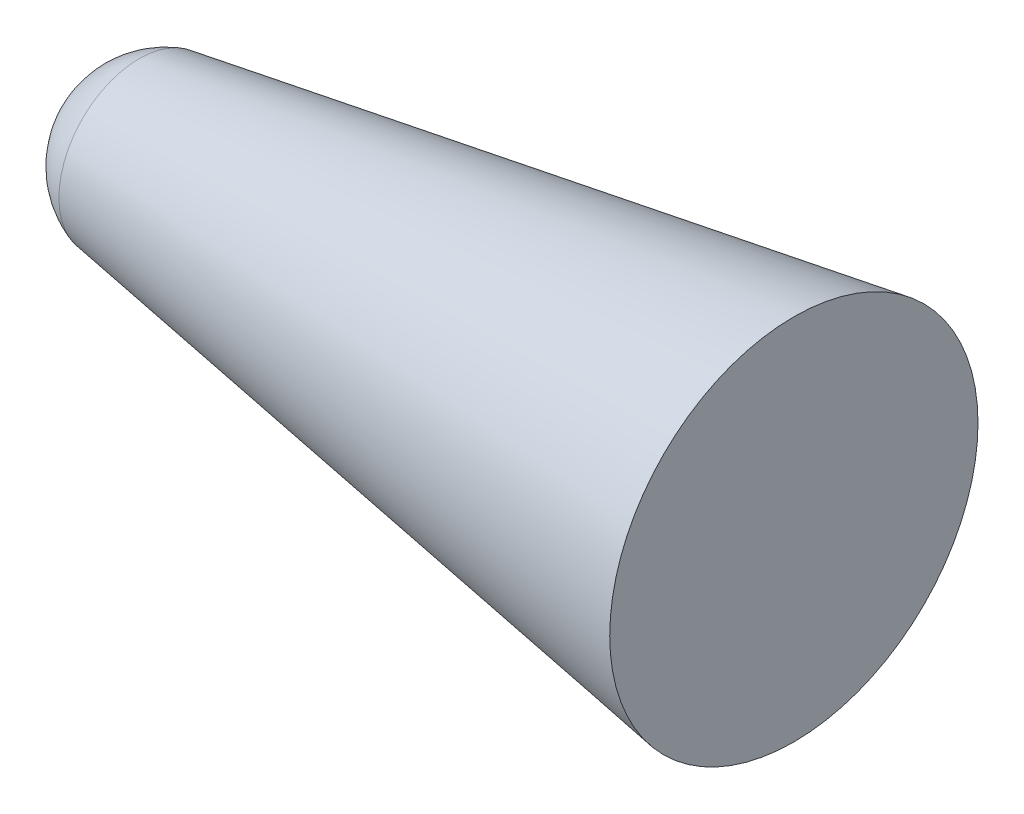
SolidWorks part; units mm, degrees
ref_plane "Front Plane" through (0, 0, 0) normal (0, 0, 1) x (1, 0, 0)
ref_plane "Top Plane" through (0, 0, 0) normal (0, 1, 0) x (1, 0, 0)
ref_plane "Right Plane" through (0, 0, 0) normal (1, 0, 0) x (0, 0, -1)
sketch "Sketch1" plane through (0, 0, 0) normal (0, 0, 1) x (1, 0, 0)
  line L0 (0, 0) -> (20.2194, 0)
  line L20 (20.2194, 0) -> (1305.2194, 0)
  line L21 (1305.2194, 0) -> (1305.2194, 331.8704)
  line L23 (125.5943, 145.0361) -> (1305.2194, 331.8704)
  arc A4 (20.2194, 0) -> (125.5943, 145.0361) centre (172.7194, 0) cw
  dimension "D1" = 1285
revolve "Revolve4" add sketch "Sketch1" angle 360 about L20
